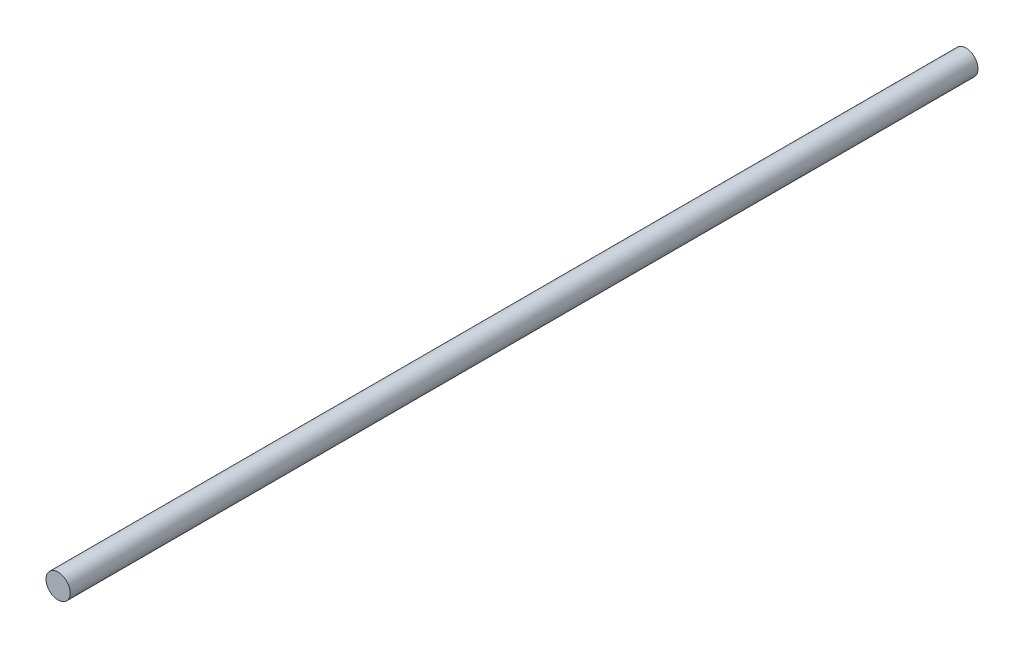
SolidWorks part; units mm, degrees
ref_plane "Front Plane" through (0, 0, 0) normal (0, 0, 1) x (1, 0, 0)
ref_plane "Top Plane" through (0, 0, 0) normal (0, 1, 0) x (1, 0, 0)
ref_plane "Right Plane" through (0, 0, 0) normal (1, 0, 0) x (0, 0, -1)
sketch "Sketch1" plane through (0, 0, 0) normal (0, 0, 1) x (1, 0, 0)
  circle A0 centre (0, 0) radius 16.25
  dimension "D1" = 32.5
extrude "Boss-Extrude1" add sketch "Sketch1" along normal blind 1219.2
